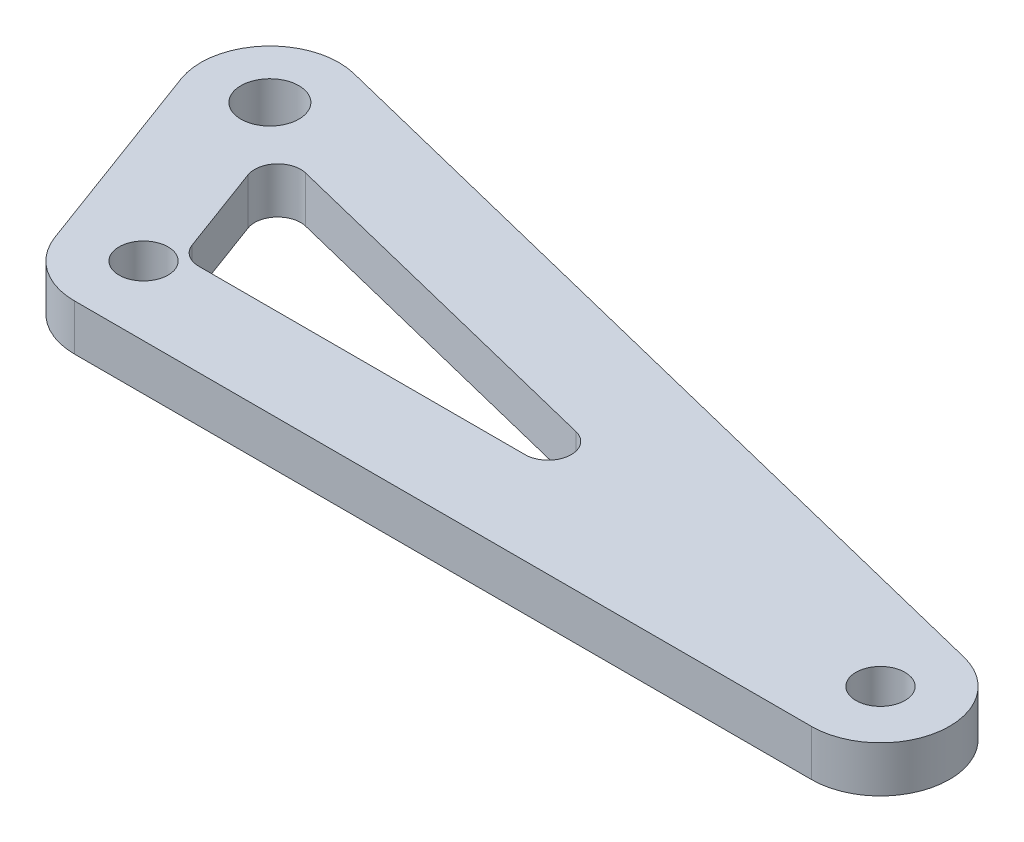
SolidWorks part; units mm, degrees
ref_plane "Front Plane" through (0, 0, 0) normal (0, 0, 1) x (1, 0, 0)
ref_plane "Top Plane" through (0, 0, 0) normal (0, 1, 0) x (1, 0, 0)
ref_plane "Right Plane" through (0, 0, 0) normal (1, 0, 0) x (0, 0, -1)
sketch "Sketch1" plane through (0, 0, 0) normal (0, 1, 0) x (1, 0, 0)
  line L0 (0, 0) -> (101.5644, 0) construction
  line L1 (101.5644, 0) -> (-10.2264, 27.6351) construction
  line L2 (-10.2264, 27.6351) -> (0, 0) construction
  line L3 (-23.321, 35.5752) -> (-7.3987, -7.4519)
  line L4 (-4.421, -9.525) -> (153.7124, -9.525)
  line L5 (154.4744, -3.2678) -> (-19.5814, 39.7594)
  line L6 (0.6524, 21.6752) -> (50.1784, 9.4322)
  line L7 (49.4165, 3.175) -> (4.421, 3.175)
  line L8 (1.4433, 5.2481) -> (-3.0872, 17.4911)
  circle A0 centre (0, 0) radius 3.3782
  circle A1 centre (-10.2264, 27.6351) radius 4
  circle A2 centre (101.5644, 0) radius 3.3782
  arc A3 (50.1784, 9.4322) -> (49.4165, 3.175) centre (49.4165, 6.35) cw
  arc A4 (4.421, 3.175) -> (1.4433, 5.2481) centre (4.421, 6.35) cw
  arc A5 (0.6524, 21.6752) -> (-3.0872, 17.4911) centre (-0.1096, 18.593) ccw
  arc A6 (154.4744, -3.2678) -> (153.7124, -9.525) centre (153.7124, -6.35) cw
  arc A7 (-4.421, -9.525) -> (-7.3987, -7.4519) centre (-4.421, -6.35) cw
  arc A8 (-19.5814, 39.7594) -> (-23.321, 35.5752) centre (-20.3433, 36.6771) ccw
  circle A9 centre (101.5644, 0) radius 9.525
  circle A10 centre (0, 0) radius 9.525
  circle A11 centre (-10.2264, 27.6351) radius 9.525
  point P18 (-0.8219, 11.3696)
  dimension "D4" = 6.7564
  dimension "D5" = 8
  dimension "D6" = 9.525
  dimension "D12" = 3.175
  dimension "D2" = 29.4665
  dimension "D3" = 115.156
  dimension "D7" = 9.525
  dimension "D8" = 9.525
  dimension "D9" = 12.7
  dimension "D10" = 12.7
  dimension "D11" = 12.7
  dimension "D13" = 101.5644
extrude "Boss-Extrude2" add sketch "Sketch1" along normal blind 6.35 contours A11 L3 A10 L8 A5 L6 A3 L7 L4 A9 L5 | A10 L7 A4 L8 A0 | A9 A2 | A11 A1
